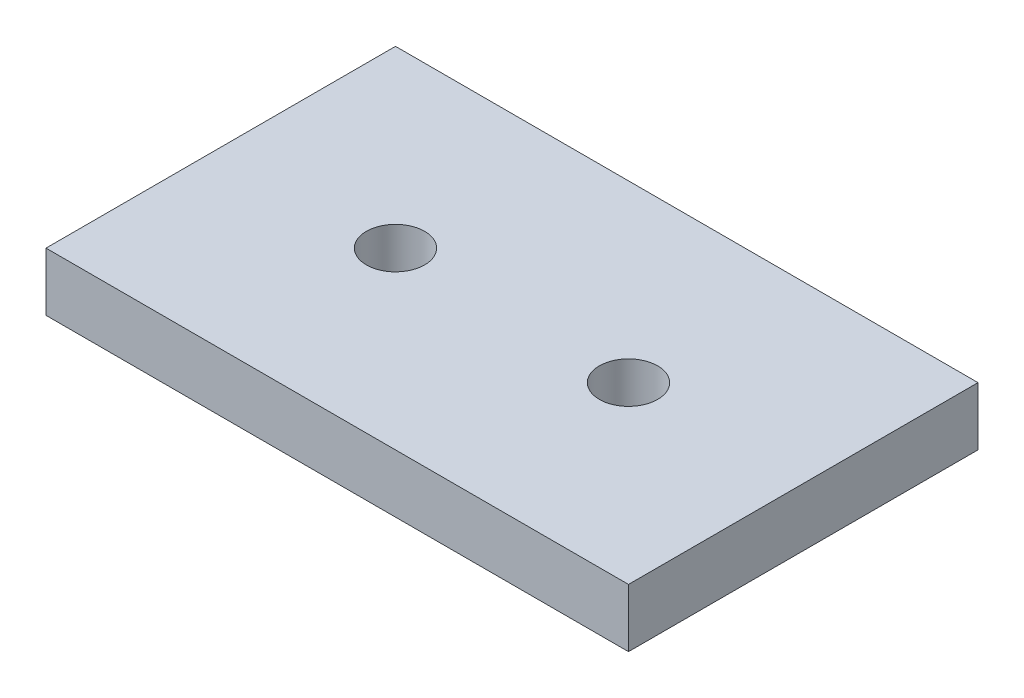
SolidWorks part; units mm, degrees
ref_plane "前视基准面" through (0, 0, 0) normal (0, 0, 1) x (1, 0, 0)
ref_plane "上视基准面" through (0, 0, 0) normal (0, 1, 0) x (1, 0, 0)
ref_plane "右视基准面" through (0, 0, 0) normal (1, 0, 0) x (0, 0, -1)
other "Configuration Table"
sketch "草图1" plane through (0, 0, 0) normal (0, 1, 0) x (1, 0, 0)
  line L1 (-50, -30) -> (50, -30)
  line L2 (-50, -30) -> (-50, 30)
  line L3 (-50, 30) -> (50, 30)
  line L4 (50, -30) -> (50, 30)
  line L5 (0, 30) -> (0, -30) construction
  line L6 (-50, 0) -> (50, 0) construction
  point P0 (0, 0)
extrude "凸台-拉伸1" add sketch "草图1" along normal blind 10
sketch "草图2" plane through (0, 0, 0) normal (0, 1, 0) x (1, 0, 0)
  circle A0 centre (-20, 0) radius 5
extrude "切除-拉伸1" cut sketch "草图2" along normal blind 20
sketch "草图3" plane through (0, 0, 0) normal (0, 1, 0) x (1, 0, 0)
  circle A0 centre (20, 0) radius 5
extrude "切除-拉伸2" cut sketch "草图3" along normal blind 20
chamfer "倒角1" distance 1 angle 45 2 edges at (20, 0, 5) (-20, 0, 5)
sketch "草图4" plane through (0, 0, 0) normal (0, 1, 0) x (1, 0, 0)
  line L0 (-10, -20) -> (10, -20)
